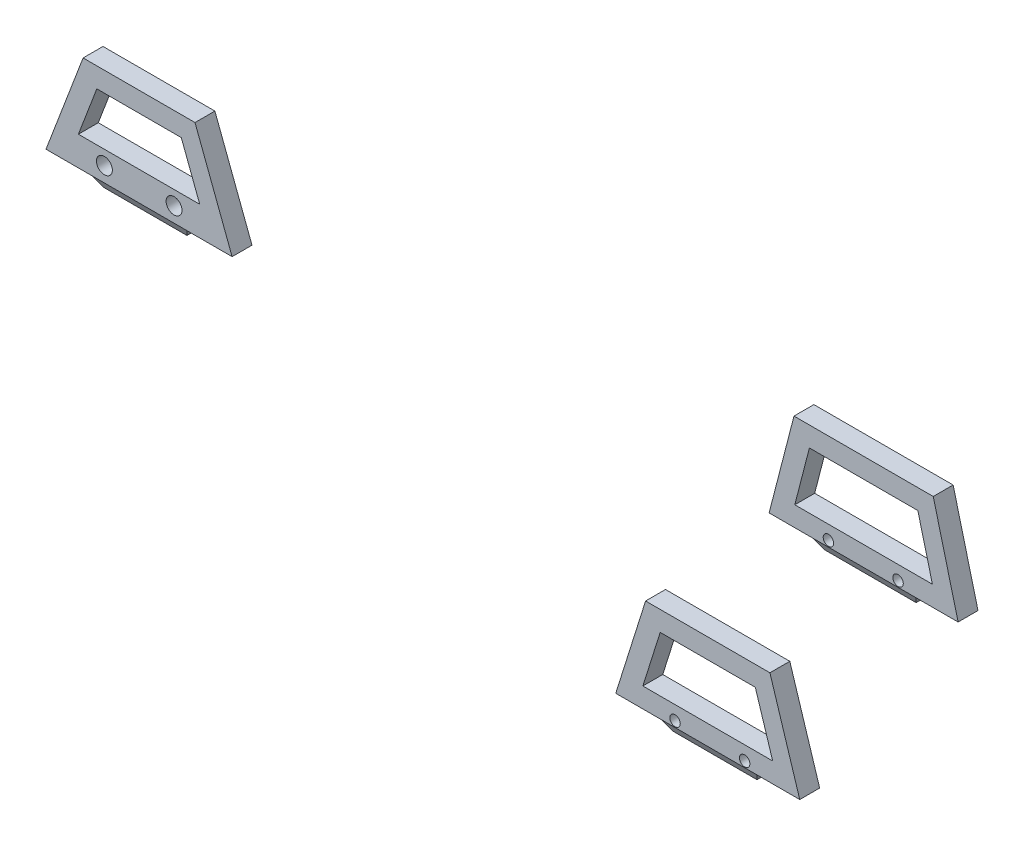
SolidWorks part; units mm, degrees
ref_plane "Front Plane" through (0, 0, 0) normal (0, 0, 1) x (1, 0, 0)
ref_plane "Top Plane" through (0, 0, 0) normal (0, 1, 0) x (1, 0, 0)
ref_plane "Right Plane" through (0, 0, 0) normal (1, 0, 0) x (0, 0, -1)
sketch "Sketch1" plane through (0, 0, 0) normal (0, 0, 1) x (1, 0, 0)
  line L0 (-55.4442, 22.0632) -> (-32.9442, 22.0632)
  line L1 (-32.9442, 22.0632) -> (-25.4837, 2.4331)
  line L3 (-55.4442, 22.0632) -> (-62.9048, 2.4331)
  line L4 (-52.6853, 18.0632) -> (-35.7032, 18.0632)
  line L5 (-35.7032, 18.0632) -> (-31.9936, 8.3027)
  line L6 (-31.9936, 8.3027) -> (-56.3949, 8.3027)
  line L7 (-56.3949, 8.3027) -> (-52.6853, 18.0632)
  line L16 (87.4954, 31.1688) -> (115.4954, 31.1688)
  line L17 (115.4954, 31.1688) -> (120.4954, 11.8038)
  line L18 (120.4954, 11.8038) -> (82.4954, 11.8038)
  line L19 (82.4954, 11.8038) -> (87.4954, 31.1688)
  line L20 (90.5938, 27.1688) -> (112.3971, 27.1688)
  line L21 (112.3971, 27.1688) -> (115.3315, 15.8038)
  line L22 (115.3315, 15.8038) -> (87.6594, 15.8038)
  line L23 (87.6594, 15.8038) -> (90.5938, 27.1688)
  line L24 (-62.9048, 2.4331) -> (-25.4837, 2.4331)
  line L25 (57.6557, -15.9504) -> (82.6557, -15.9504)
  line L26 (82.6557, -15.9504) -> (88.6557, -35.0292)
  line L27 (88.6557, -35.0292) -> (51.6557, -35.0292)
  line L28 (51.6557, -35.0292) -> (57.6557, -15.9504)
  line L29 (60.5909, -19.9504) -> (79.7206, -19.9504)
  line L30 (79.7206, -19.9504) -> (83.2047, -31.0292)
  line L31 (83.2047, -31.0292) -> (57.1068, -31.0292)
  line L32 (57.1068, -31.0292) -> (60.5909, -19.9504)
  circle A0 centre (-51.1597, 5.4578) radius 1.6
  circle A1 centre (-37.1597, 5.4587) radius 1.6
  circle A2 centre (94.4203, 12.9998) radius 1.05
  circle A5 centre (108.4203, 12.9998) radius 1.05
  circle A6 centre (63.5806, -33.8333) radius 1.05
  circle A7 centre (77.5806, -33.8333) radius 1.05
  dimension "D32" = 14
  dimension "D35" = 110.81
  dimension "D4" = 25
  dimension "D1" = 22.5
  dimension "D2" = 21
  dimension "D3" = 21
  dimension "D5" = 4
  dimension "D6" = 20
  dimension "D7" = 4
  dimension "D8" = 4
  dimension "D9" = 4
  dimension "D10" = 4
  dimension "D22" = 28
  dimension "D23" = 20
  dimension "D24" = 20
  dimension "D25" = 38
  dimension "D26" = 4
  dimension "D27" = 4
  dimension "D28" = 4
  dimension "D29" = 4
  dimension "D30" = 4
  dimension "D31" = 4
  dimension "D34" = 14
  dimension "D36" = 110.81
  dimension "D37" = 110.81
  dimension "D38" = 110.81
  dimension "D39" = 20
  dimension "D40" = 37
  dimension "D41" = 4
  dimension "D42" = 4
  dimension "D43" = 4
  dimension "D44" = 4
  dimension "D45" = 4
  dimension "D46" = 4
  dimension "D47" = 14
extrude "Boss-Extrude1" add sketch "Sketch1" along normal blind 4
sketch "Sketch2" plane through (0, 2.4331, 0) normal (0, -1, 0) x (1, 0, 0)
  line L0 (-62.9048, 4) -> (-25.4837, 4) construction
  line L1 (-53.7087, 4) -> (-34.5673, 4)
  line L2 (-53.7087, 4) -> (-53.7087, 0)
  line L3 (-53.7087, 0) -> (-34.5673, 0)
  line L4 (-34.5673, 4) -> (-34.5673, 0)
  line L5 (-62.9048, 0) -> (-25.4837, 0) construction
extrude "Boss-Extrude2" add sketch "Sketch2" along normal blind 2 draft 30
sketch "Sketch3" plane through (0, 11.8038, 0) normal (0, -1, 0) x (1, 0, 0)
  line L0 (82.4954, 4) -> (120.4954, 4) construction
  line L1 (91.2534, 4) -> (112.0611, 4)
  line L2 (91.2534, 4) -> (91.2534, 0)
  line L3 (91.2534, 0) -> (112.0611, 0)
  line L4 (112.0611, 4) -> (112.0611, 0)
  line L5 (82.4954, 0) -> (120.4954, 0) construction
extrude "Boss-Extrude3" add sketch "Sketch3" along normal blind 2 draft 30
sketch "Sketch4" plane through (0, -35.0292, 0) normal (0, -1, 0) x (1, 0, 0)
  line L0 (51.6557, 4) -> (88.6557, 4) construction
  line L1 (60.7825, 4) -> (80.0558, 4)
  line L2 (60.7825, 4) -> (60.7825, 0)
  line L3 (60.7825, 0) -> (80.0558, 0)
  line L4 (80.0558, 4) -> (80.0558, 0)
  line L5 (51.6557, 0) -> (88.6557, 0) construction
extrude "Boss-Extrude4" add sketch "Sketch4" along normal blind 2 draft 30
